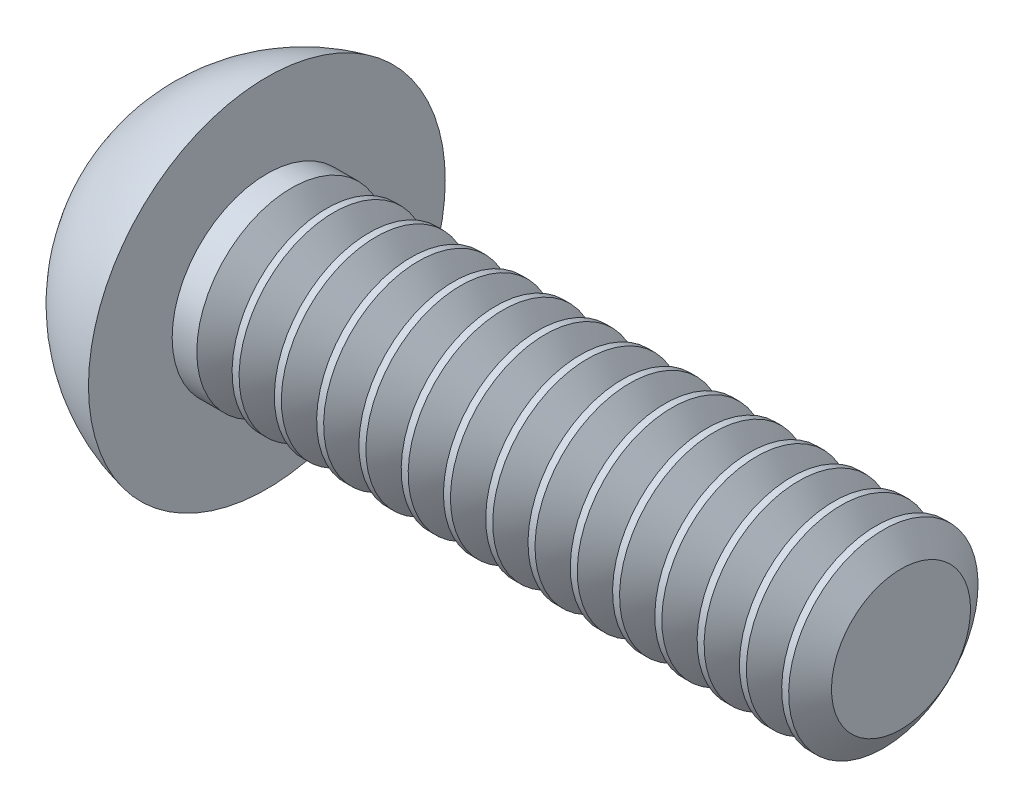
SolidWorks part; units mm, degrees
ref_plane "Plane1" through (0, 0, 0) normal (0, 0, 1) x (1, 0, 0)
ref_plane "Plane2" through (0, 0, 0) normal (0, 1, 0) x (1, 0, 0)
ref_plane "Plane3" through (0, 0, 0) normal (1, 0, 0) x (0, 0, -1)
sketch "BodySke" plane through (0, 0, 0) normal (0, 0, 1) x (1, 0, 0)
  line L0 (0, 0) -> (82.55, 0) construction
  line L1 (11.7094, 0) -> (11.7094, 1.4224)
  line L2 (11.7094, 1.4224) -> (2.1844, 1.4224)
  line L3 (2.1844, 1.4224) -> (2.1844, 2.6797)
  line L4 (11.7094, -1.4224) -> (2.1844, -1.4224) construction
  line L5 (2.1844, -1.4224) -> (2.1844, -2.6797) construction
  line L6 (2.8194, 12.7) -> (2.8194, -3.175) construction
  line L7 (11.7094, 0) -> (0, 0)
  line L8 (2.1844, 12.7) -> (2.1844, -3.175) construction
  arc A0 (0, 0) -> (2.1844, 2.6797) centre (2.7359, 0) cw
  dimension "Head_ht" = 2.1844
  dimension "Diameter" = 2.8448
  dimension "Head_dia" = 5.3594
  dimension "Length" = 9.525
  dimension "Thread_nom" = 9.525
  dimension "Advance" = 0.635
revolve "Base-Revolve" add sketch "BodySke"
cosmetic thread "ThreadCosmetic" [suppressed]
revolve "ThreadSchematic" cut sketch "ThdSchSke" angle 360 about L3
sketch "ThdSchSke" plane through (0, 0, 0) normal (0, 0, 1) x (1, 0, 0)
  line L0 (2.8194, -1.0439) -> (2.5544, -1.4224)
  line L1 (2.8194, -1.0439) -> (3.0844, -1.4224)
  line L2 (3.0844, -1.4224) -> (3.0844, -1.778)
  line L3 (-3.175, 0) -> (5.1513, 0) construction
  line L5 (3.0844, -1.778) -> (2.5544, -1.778)
  line L6 (2.5544, -1.778) -> (2.5544, -1.4224)
  dimension "Diameter" = 2.8448
  dimension "SideAngle" = 55
  dimension "VeeAngle" = 70
  dimension "Thread_minor" = 2.0879
  dimension "Overcut" = 3.556
  dimension "Start" = 2.8194
sketch "Sketch2" plane through (0, 0, 0) normal (1, 0, 0) x (0, 0, -1)
  line L0 (2.6797, 0.4953) -> (-2.6797, 0.4953)
  line L1 (2.6797, 0.4953) -> (2.6797, -0.4953)
  line L2 (-2.6797, -0.4953) -> (2.6797, -0.4953)
  line L3 (-2.6797, -0.4953) -> (-2.6797, 0.4953)
  dimension "D1" = 5.3594
  dimension "Slot_width" = 0.9906
  dimension "D2" = 2.6797
  dimension "D3" = 0.4953
extrude "Slot" [suppressed] cut sketch "Sketch2" along normal blind 1.4732
sketch "Sketch3" plane through (0, 0, 0) normal (1, 0, 0) x (0, 0, -1)
  line L0 (0.3683, -1.7399) -> (-0.3683, -1.7399)
  line L1 (0.3683, -1.7399) -> (0.3683, 1.7399)
  line L2 (-0.3683, 1.7399) -> (0.3683, 1.7399)
  line L3 (-0.3683, 1.7399) -> (-0.3683, -1.7399)
  dimension "Cross_width" = 0.7366
  dimension "D1" = 0.3683
  dimension "Cross_dia" = 3.4798
  dimension "D2" = 1.7399
ref_plane "Plane4" through (1.9558, 0, 0) normal (1, 0, 0) x (0, 0, -1)
sketch "Sketch4" plane through (1.9558, 0, 0) normal (1, 0, 0) x (0, 0, -1)
  line L0 (0.1842, -0.1842) -> (-0.1841, -0.1842)
  line L1 (0.1842, -0.1842) -> (0.1842, 0.1842)
  line L2 (-0.1841, 0.1841) -> (0.1842, 0.1842)
  line L3 (-0.1841, 0.1841) -> (-0.1841, -0.1842)
  dimension "D1" = 0.3683
  dimension "D2" = 0.1842
  dimension "D3" = 0.3683
  dimension "D4" = 0.1842
loft "Cross" cut profiles "Sketch3", "Sketch4"
pattern_circular "CirPattern1" count 2 every 90 about axis through (0, 0, 0) along (1, 0, 0) of "Cross"
pattern_linear "ThdSchPat" count 15 spacing 0.635 along (1, 0, 0) of "ThreadSchematic"
equation "\"D1@Sketch2\" = \"Head_dia@BodySke\""
equation "\"D2@Sketch2\" = \"D1@Sketch2\" / 2"
equation "\"D3@Sketch2\" = \"Slot_width@Sketch2\" / 2"
equation "\"D1@Sketch3\" = \"Cross_width@Sketch3\" / 2"
equation "\"D2@Sketch3\" = \"Cross_dia@Sketch3\" / 2"
equation "\"D1@Sketch4\" = \"Cross_width@Sketch3\" *.5"
equation "\"D2@Sketch4\" = \"D1@Sketch4\" / 2"
equation "\"D3@Sketch4\" = \"D1@Sketch4\""
equation "\"D4@Sketch4\" = \"D2@Sketch4\""
equation "\"Thread_length@ThreadCosmetic\" = ((sgn( (\"Length@BodySke\" - \"Advance@BodySke\" ) - \"Thread_nom@BodySke\" )-1)*( (\"Length@BodySke\" - \"Advance@BodySke\" ) - \"Thread_nom@BodySke\" ))/-2+ \"Thread_nom@BodySke\""
equation "\"Thread_minor@ThdSchSke\" = \"Thread_minor@ThreadCosmetic\""
equation "\"Diameter@ThdSchSke\" = \"Diameter@BodySke\""
equation "\"Overcut@ThdSchSke\" = \"Diameter@BodySke\" * 1.25"
equation "\"Start@ThdSchSke\" = \"Head_ht@BodySke\" + \"Length@BodySke\" - \"Thread_length@ThreadCosmetic\"  '---Non-countersunk---"
equation "\"Num_threads@ThdSchPat\" = int( \"Thread_length@ThreadCosmetic\" / \"Advance@BodySke\" + 0.999 )  + 1"
equation "\"Advance@ThdSchPat\" = \"Thread_length@ThreadCosmetic\" /  (\"Num_threads@ThdSchPat\" - 1) 'relax it"
